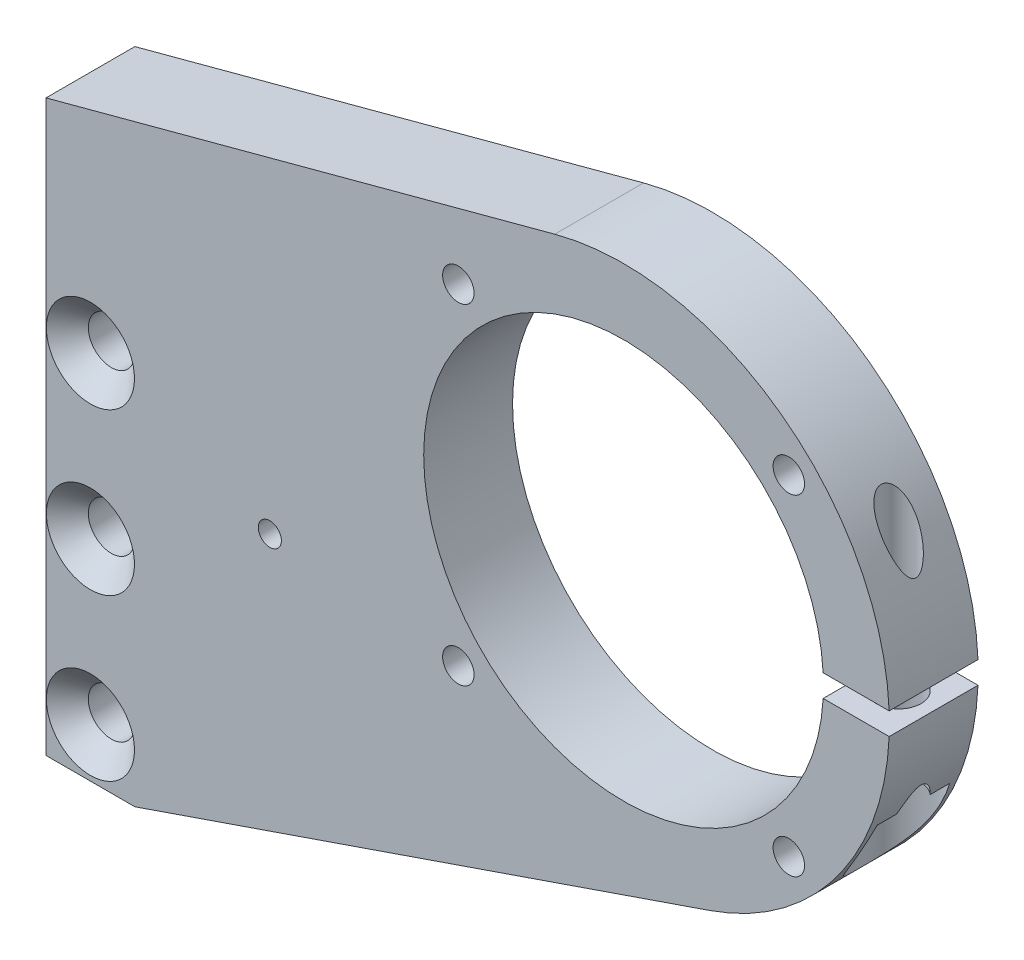
SolidWorks part; units mm, degrees
ref_plane "Front Plane" through (0, 0, 0) normal (0, 0, 1) x (1, 0, 0)
ref_plane "Top Plane" through (0, 0, 0) normal (0, 1, 0) x (1, 0, 0)
ref_plane "Right Plane" through (0, 0, 0) normal (1, 0, 0) x (0, 0, -1)
ref_plane "Plane1" through (0, 0, 0) normal (0, 0, -1) x (-1, 0, 0)
sketch "Sketch1" plane through (0, 0, 0) normal (0, 0, -1) x (-1, 0, 0)
  line L0 (224.1695, 127.7225) -> (151.4352, 147.2116)
  line L1 (129.2465, 74.5705) -> (211.4695, 46.305)
  line L2 (211.4695, 46.305) -> (224.1695, 46.305)
  line L3 (224.1695, 46.305) -> (224.1695, 127.7225)
  arc A0 (151.4352, 147.2116) -> (129.2465, 74.5705) centre (141.6001, 110.5064) ccw
extrude "Boss-Extrude1" add sketch "Sketch1" against normal blind 12.7
sketch "Sketch2" plane through (0, 0, 12.7) normal (0, 0, 1) x (1, 0, 0)
  line L0 (-103.6333, 112.0939) -> (-113.179, 112.0939)
  line L1 (-113.179, 108.9189) -> (-103.6333, 108.9189)
  arc A0 (-103.6333, 108.9189) -> (-103.6333, 112.0939) centre (-141.6001, 110.5064) ccw
  arc A1 (-113.179, 112.0939) -> (-113.179, 108.9189) centre (-141.6001, 110.5064) cw
extrude "Cut-Extrude1" cut sketch "Sketch2" against normal through all
ref_plane "Plane2" through (0, 110.5064, 0) normal (0, 1, 0) x (1, 0, 0)
sketch "Sketch3" plane through (0, 110.5064, 0) normal (0, 1, 0) x (1, 0, 0)
  line L0 (-113.0251, 0) -> (-141.6001, 0)
  line L1 (-141.6001, 0) -> (-141.6001, -12.7)
  line L2 (-141.6001, -12.7) -> (-113.0251, -12.7)
  line L3 (-113.0251, -12.7) -> (-113.0251, 0)
  line L4 (-141.6001, 0) -> (-141.6001, -12.7) construction
  dimension "D1" = 28.575
revolve "Cut-Revolve1" cut sketch "Sketch3" angle 360 about L4
hole_wizard "#8 Clearance Hole1" positions "Sketch5" profile "Sketch4" hole size "#8" standard "ANSI Inch"
sketch "Sketch5" plane through (0, 0, 12.7) normal (0, 0, 1) x (1, 0, 0)
  line L0 (-141.6001, 139.0814) -> (-141.6001, 81.9314) construction
  arc A0 (-113.0692, 112.0939) -> (-113.0692, 108.9189) centre (-141.6001, 110.5064) ccw construction
  point P0 (-117.9781, 86.8844)
  point P1 (-165.2221, 86.8844)
  point P2 (-165.2221, 134.1284)
  point P3 (-117.9781, 134.1284)
  point P12 (-141.6001, 110.5064)
  dimension "D1" = 47.244
  dimension "D2" = 47.244
  dimension "D3" = 23.622
  dimension "D4" = 47.244
  dimension "D5" = 23.622
  dimension "D6" = 23.622
  dimension "D7" = 47.244
  dimension "D8" = 23.622
sketch "Sketch4" plane through (-117.9781, 86.8844, 12.7) normal (1, 0, 0) x (0, -1, 0)
  line L0 (0, 0) -> (0, 12.7)
  line L1 (0, 12.7) -> (2.25, 12.7)
  line L2 (2.25, 12.7) -> (2.25, 0)
  line L5 (2.25, 0) -> (0, 0)
  line L11 (0, -6.35) -> (0, 107.95) construction
  dimension "Thru Hole Dia." = 4.5
  dimension "Thru Hole Depth" = 12.7
hole_wizard "1/4 Clearance Hole1" positions "Sketch7" profile "Sketch6" hole size "1/4" standard "ANSI Inch"
sketch "Sketch7" plane through (0, 0, 0) normal (0, 0, -1) x (-1, 0, 0)
  point P0 (217.8195, 53.305)
  point P1 (217.8195, 76.305)
  point P2 (217.8195, 99.305)
sketch "Sketch6" plane through (-217.8195, 53.305, 0) normal (1, 0, 0) x (0, 1, 0)
  line L0 (0, 0) -> (0, 12.7)
  line L1 (0, 12.7) -> (3.3, 12.7)
  line L2 (3.3, 12.7) -> (3.3, 0)
  line L5 (3.3, 0) -> (0, 0)
  line L11 (0, -6.35) -> (0, 107.95) construction
  dimension "Thru Hole Dia." = 6.6
  dimension "Thru Hole Depth" = 12.7
hole_wizard "#12 Clearance Hole1" positions "Sketch9" profile "Sketch8" hole size "#12" standard "ANSI Inch"
sketch "Sketch9" plane through (0, 0, 12.7) normal (0, 0, 1) x (1, 0, 0)
  point P0 (-192.1695, 89.7225)
sketch "Sketch8" plane through (-192.1695, 89.7225, 12.7) normal (1, 0, 0) x (0, -1, 0)
  line L0 (0, 0) -> (0, 12.7)
  line L1 (0, 12.7) -> (3, 12.7)
  line L2 (3, 12.7) -> (3, 0)
  line L5 (3, 0) -> (0, 0)
  line L11 (0, -6.35) -> (0, 107.95) construction
  dimension "Thru Hole Dia." = 6
  dimension "Thru Hole Depth" = 12.7
ref_plane "Plane3" through (0, 84.1425, 0) normal (0, -1, 0) x (-1, 0, 0)
hole_wizard "Hole1" positions "Sketch11" profile "Sketch10" legacy
sketch "Sketch11" plane through (0, 84.1425, 0) normal (0, -1, 0) x (-1, 0, 0)
  point P0 (108.6333, -6.35)
sketch "Sketch10" plane through (-108.6333, 84.1425, 6.35) normal (1, 0, 0) x (0, 0, -1)
  line L0 (0, 0) -> (0, 24.7764)
  line L1 (0, 24.7764) -> (3.2, 24.7764)
  line L2 (3.2, 24.7764) -> (3.2, 11.7764)
  line L3 (3.2, 11.7764) -> (5.6, 11.7764)
  line L4 (5.6, 11.7764) -> (5.6, 0)
  line L5 (5.6, 0) -> (0, 0)
  line L6 (0, 110) -> (0, -10) construction
  dimension "Diameter" = 6.4
  dimension "Depth" = 24.7764
  dimension "C-Bore Diameter" = 11.2
  dimension "C-Bore Depth" = 11.7764
hole_wizard "#10 Clearance Hole1" positions "Sketch13" profile "Sketch12" hole size "#10" standard "ANSI Inch"
sketch "Sketch13" plane through (0, 112.0939, 0) normal (0, -1, 0) x (-1, 0, 0)
  point P0 (108.6333, -6.35)
sketch "Sketch12" plane through (-108.6333, 112.0939, 6.35) normal (1, 0, 0) x (0, 0, -1)
  line L0 (0, 0) -> (0, 36.4125)
  line L1 (0, 36.4125) -> (2.5, 36.4125)
  line L2 (2.5, 36.4125) -> (2.5, 0)
  line L5 (2.5, 0) -> (0, 0)
  line L11 (0, -6.35) -> (0, 107.95) construction
  dimension "Thru Hole Dia." = 5
  dimension "Thru Hole Depth" = 36.4125
sketch "Sketch14" plane through (0, 0, 0) normal (0, 0, -1) x (-1, 0, 0)
  circle A0 centre (192.1695, 89.7225) radius 1.651
  circle A1 centre (192.1695, 89.7225) radius 3 construction
  circle A2 centre (192.1695, 89.7225) radius 3
  point P0 (192.1695, 89.7225)
  dimension "D1" = 3.302
extrude "Boss-Extrude2" add sketch "Sketch14" against normal up to surface (12.7 mm away) up to face at (-189.1695, 89.7225, 12.7)
sketch "草图1" plane through (0, 0, 12.7) normal (0, 0, 1) x (1, 0, 0)
  circle A0 centre (-217.8195, 99.305) radius 6.3
  circle A1 centre (-217.8195, 76.305) radius 6.3
  circle A2 centre (-217.8195, 53.305) radius 6.3
  dimension "D1" = 12.6
extrude "切除-拉伸1" cut sketch "草图1" against normal blind 3 draft 45
